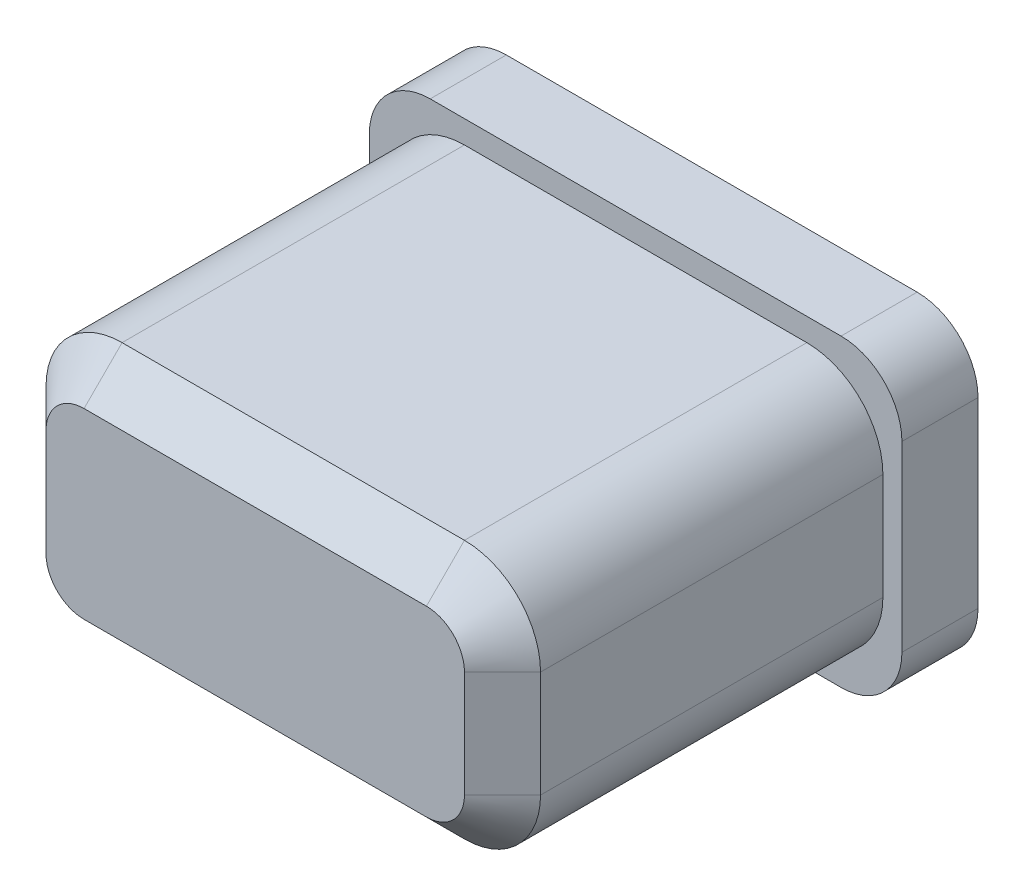
SolidWorks part; units mm, degrees
ref_plane "前视基准面" through (0, 0, 0) normal (0, 0, 1) x (1, 0, 0)
ref_plane "上视基准面" through (0, 0, 0) normal (0, 1, 0) x (1, 0, 0)
ref_plane "右视基准面" through (0, 0, 0) normal (1, 0, 0) x (0, 0, -1)
sketch "草图1" plane through (0, 0, 0) normal (0, 0, 1) x (1, 0, 0)
  line L1 (-3.25, 1.7) -> (3.25, 1.7)
  line L2 (-3.25, 1.7) -> (-3.25, -1.7)
  line L3 (-3.25, -1.7) -> (3.25, -1.7)
  line L4 (3.25, 1.7) -> (3.25, -1.7)
  line L5 (-3.25, 1.7) -> (3.25, -1.7) construction
  line L6 (-3.25, -1.7) -> (3.25, 1.7) construction
  point P0 (0, 0)
  dimension "D1" = 6.5
  dimension "D2" = 3.4
extrude "凸台-拉伸1" add sketch "草图1" along normal blind 5
fillet "圆角1" radius 1 4 edges at (-3.25, 1.7, 2.5) (3.25, 1.7, 2.5) (3.25, -1.7, 2.5) (-3.25, -1.7, 2.5)
chamfer "倒角1" distance 0.5 angle 45 8 edges at (2.9571, 1.4071, 5) (3.25, 0, 5) (2.9571, -1.4071, 5) (0, -1.7, 5) (-2.9571, -1.4071, 5) (-3.25, 0, 5) (-2.9571, 1.4071, 5) (0, 1.7, 5)
sketch "草图2" plane through (0, 0, 0) normal (0, 0, -1) x (-1, 0, 0)
  line L1 (3.5, 2) -> (-3.5, 2)
  line L2 (3.5, 2) -> (3.5, -2)
  line L3 (3.5, -2) -> (-3.5, -2)
  line L4 (-3.5, 2) -> (-3.5, -2)
  line L5 (3.5, 2) -> (-3.5, -2) construction
  line L6 (3.5, -2) -> (-3.5, 2) construction
  point P0 (0, 0)
  dimension "D1" = 4
  dimension "D2" = 7
extrude "凸台-拉伸2" add sketch "草图2" along normal blind 1
fillet "圆角2" radius 0.8 4 edges at (3.5, 2, -0.5) (3.5, -2, -0.5) (-3.5, -2, -0.5) (-3.5, 2, -0.5)
